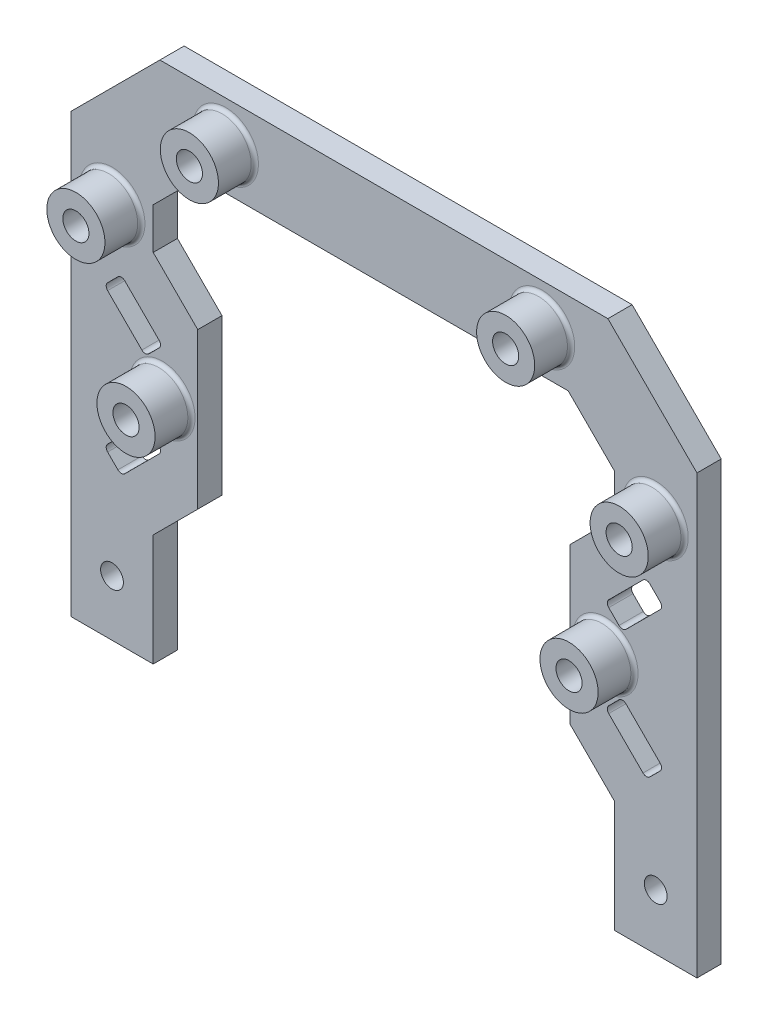
SolidWorks part; units mm, degrees
ref_plane "Front Plane" through (0, 0, 0) normal (0, 0, 1) x (1, 0, 0)
ref_plane "Top Plane" through (0, 0, 0) normal (0, 1, 0) x (1, 0, 0)
ref_plane "Right Plane" through (0, 0, 0) normal (1, 0, 0) x (0, 0, -1)
sketch "Sketch2" plane through (0, 0, 0) normal (0, 0, 1) x (1, 0, 0)
  line L0 (-64.5954, 0) -> (64.5954, 0) construction
  line L2 (-36.0554, 88.6243) -> (36.0554, 88.6243) construction
  line L3 (-38.6151, 31.7729) -> (-47.1004, 23.2876) construction
  line L4 (-47.1004, 73.3367) -> (-38.6151, 64.8514) construction
  line L6 (0, 0) -> (0, 120.7475) construction
  line L8 (-38.0349, 91.6243) -> (0, 91.6243)
  line L9 (-46.2156, 108.6243) -> (0, 108.6243)
  line L14 (46.2156, 108.6243) -> (0, 108.6243)
  line L15 (38.0349, 91.6243) -> (0, 91.6243)
  line L16 (-57.3534, 54.5983) -> (-42.8577, 69.094) construction
  line L21 (-42.8577, 27.5303) -> (-57.3534, 42.026) construction
  line L22 (42.8577, 27.5303) -> (57.3534, 42.026) construction
  line L23 (-46.2156, 108.6243) -> (-64.5954, 90.2445)
  line L24 (-47.5954, 73.5488) -> (-47.5954, 82.0638)
  line L25 (-38.0349, 91.6243) -> (-47.5954, 82.0638)
  line L26 (-64.5954, 0) -> (-47.5954, 0)
  line L27 (-38.403, 64.3564) -> (-38.403, 32.2679)
  line L28 (-47.5954, 23.0755) -> (-38.403, 32.2679)
  line L29 (-38.403, 64.3564) -> (-47.5954, 73.5488)
  line L30 (-47.5954, 23.0755) -> (-47.5954, 0)
  line L31 (-64.5954, 0) -> (-64.5954, 90.2445)
  line L32 (42.7586, 68.9949) -> (57.3534, 54.5983) construction
  line L33 (64.5954, 0) -> (64.5954, 90.2445)
  line L34 (47.5954, 23.0755) -> (47.5954, 0)
  line L35 (38.403, 64.3564) -> (47.5954, 73.5488)
  line L36 (47.5954, 23.0755) -> (38.403, 32.2679)
  line L37 (38.403, 64.3564) -> (38.403, 32.2679)
  line L38 (64.5954, 0) -> (47.5954, 0)
  line L39 (38.0349, 91.6243) -> (47.5954, 82.0638)
  line L40 (47.5954, 73.5488) -> (47.5954, 82.0638)
  line L41 (46.2156, 108.6243) -> (64.5954, 90.2445)
  line L42 (-53.1108, 46.2686) -> (-61.5961, 37.7833) construction
  line L43 (-61.5961, 58.841) -> (-53.1108, 50.3557) construction
  point P34 (0, 0)
  point P38 (0, 108.6243)
  point P39 (0, 91.6243)
  point P40 (-42.9992, 27.6717)
  dimension "D2" = 17
  dimension "D4" = 13
  dimension "D3" = 0.2
  dimension "D5" = 17
  dimension "D6" = 45
  dimension "D7" = 13
  dimension "D8" = 3
  dimension "D10" = 0.2
extrude "Boss-Extrude2" add sketch "Sketch2" against normal blind 5
sketch "Sketch4" plane through (0, 0, 0) normal (0, 0, 1) x (1, 0, 0)
  line L0 (56.0954, 0) -> (55.4055, 99.4344) construction
  line L1 (55.4055, 99.4344) -> (-55.4055, 99.4344) construction
  line L2 (-55.4055, 99.4344) -> (-56.0954, 0) construction
  line L3 (-38.403, 48.3122) -> (-64.4972, 48.3122) construction
  line L4 (38.403, 48.3122) -> (64.4972, 48.3122) construction
  line L5 (38.403, 64.3564) -> (38.403, 32.2679) construction
  line L6 (-47.5954, 0) -> (-64.5954, 0) construction
  line L8 (-46.2156, 108.6243) -> (-64.5954, 90.2445) construction
  line L9 (64.5954, 90.2445) -> (46.2156, 108.6243) construction
  line L10 (-38.403, 32.2679) -> (-38.403, 64.3564) construction
  line L11 (42.9992, 27.6717) -> (42.9992, 68.9526) construction
  line L12 (47.5954, 73.5488) -> (38.403, 64.3564) construction
  line L13 (38.403, 32.2679) -> (47.5954, 23.0755) construction
  line L14 (47.5954, 77.8063) -> (64.4972, 77.8063) construction
  line L15 (47.5954, 82.0638) -> (47.5954, 73.5488) construction
  line L16 (31.2176, 108.8703) -> (31.2176, 91.6243) construction
  line L17 (0, 108.6243) -> (0, 91.6243) construction
  line L19 (47.5954, 0) -> (64.5954, 0) construction
  circle A0 centre (45.703, 48.3122) radius 6
  circle A1 centre (56.0463, 77.8063) radius 6
  circle A2 centre (32.6276, 100.1896) radius 6
  circle A3 centre (-32.6276, 100.1896) radius 6
  circle A4 centre (-45.703, 48.3122) radius 6
  circle A5 centre (-56.0463, 77.8063) radius 6
  point P11 (56.0463, 77.8063)
  dimension "D1" = 12
  dimension "D3" = 7.3
  dimension "D2" = 12
  dimension "D5" = 12
  dimension "D4" = 15
extrude "Boss-Extrude3" add sketch "Sketch4" along normal blind 7.5
fillet "Fillet1" radius 0.75 6 edges at (26.6276, 100.1896, 0) (50.0463, 77.8063, 0) (39.703, 48.3122, 0) (-51.703, 48.3122, 0) (-62.0463, 77.8063, 0) (-38.6276, 100.1896, 0)
sketch "Sketch5" plane through (0, 0, -5) normal (0, 0, -1) x (-1, 0, 0)
  circle A0 centre (56.0954, 11.5) radius 2.35 construction
  circle A1 centre (-56.0954, 11.5) radius 2.35 construction
  circle A2 centre (56.0954, 11.5) radius 2.35
  circle A3 centre (-56.0954, 11.5) radius 2.35
extrude "Cut-Extrude1" cut sketch "Sketch5" against normal up to surface (5 mm away) up to face at (25.8776, 100.1896, 0)
sketch "Sketch6" plane through (0, 0, 7.5) normal (0, 0, 1) x (1, 0, 0)
  circle A0 centre (32.6276, 100.1896) radius 6 construction
  circle A1 centre (45.703, 48.3122) radius 6 construction
  circle A2 centre (56.0463, 77.8063) radius 6 construction
  circle A3 centre (-32.6276, 100.1896) radius 6 construction
  circle A4 centre (-56.0463, 77.8063) radius 6 construction
  circle A5 centre (-45.703, 48.3122) radius 6 construction
  circle A6 centre (32.6276, 100.1896) radius 6 construction
  circle A7 centre (45.703, 48.3122) radius 6 construction
  circle A8 centre (56.0463, 77.8063) radius 6 construction
  circle A9 centre (-32.6276, 100.1896) radius 6 construction
  circle A10 centre (-56.0463, 77.8063) radius 6 construction
  circle A11 centre (-45.703, 48.3122) radius 6 construction
  circle A12 centre (-45.703, 48.3122) radius 2.7
  circle A14 centre (-32.6276, 100.1896) radius 2.7
  circle A15 centre (32.6276, 100.1896) radius 2.7
  circle A16 centre (56.0463, 77.8063) radius 2.7
  circle A17 centre (45.703, 48.3122) radius 2.7
  circle A18 centre (-56.0463, 77.8063) radius 2.7
  dimension "D1" = 5.4
extrude "Cut-Extrude2" cut sketch "Sketch6" against normal up to surface (12.5 mm away) up to face at (-58.4454, 11.5, -5)
sketch "Sketch7" plane through (0, 0, -5) normal (0, 0, -1) x (-1, 0, 0)
  line L0 (45.6862, 57.7803) -> (49.2217, 54.2448) construction
  line L1 (49.2217, 54.2448) -> (57.707, 62.7301) construction
  line L2 (57.707, 62.7301) -> (54.1715, 66.2656) construction
  line L3 (54.1715, 66.2656) -> (45.6862, 57.7803) construction
  line L4 (54.1715, 30.3587) -> (57.707, 33.8943) construction
  line L5 (57.707, 33.8943) -> (49.2217, 42.3795) construction
  line L6 (49.2217, 42.3795) -> (45.6862, 38.844) construction
  line L7 (45.6862, 38.844) -> (54.1715, 30.3587) construction
  line L8 (-54.1715, 66.2656) -> (-57.707, 62.7301) construction
  line L9 (-57.707, 62.7301) -> (-49.2217, 54.2448) construction
  line L10 (-49.2217, 54.2448) -> (-45.6862, 57.7803) construction
  line L11 (-45.6862, 57.7803) -> (-54.1715, 66.2656) construction
  line L12 (-45.6862, 38.844) -> (-49.2217, 42.3795) construction
  line L13 (-49.2217, 42.3795) -> (-57.707, 33.8943) construction
  line L14 (-57.707, 33.8943) -> (-54.1715, 30.3587) construction
  line L15 (-54.1715, 30.3587) -> (-45.6862, 38.844) construction
  line L16 (45.6862, 57.7803) -> (49.2217, 54.2448)
  line L17 (49.2217, 54.2448) -> (57.707, 62.7301)
  line L18 (57.707, 62.7301) -> (54.1715, 66.2656)
  line L19 (54.1715, 66.2656) -> (45.6862, 57.7803)
  line L20 (54.1715, 30.3587) -> (57.707, 33.8943)
  line L21 (57.707, 33.8943) -> (49.2217, 42.3795)
  line L22 (49.2217, 42.3795) -> (45.6862, 38.844)
  line L23 (45.6862, 38.844) -> (54.1715, 30.3587)
  line L24 (-54.1715, 66.2656) -> (-57.707, 62.7301)
  line L25 (-57.707, 62.7301) -> (-49.2217, 54.2448)
  line L26 (-49.2217, 54.2448) -> (-45.6862, 57.7803)
  line L27 (-45.6862, 57.7803) -> (-54.1715, 66.2656)
  line L28 (-45.6862, 38.844) -> (-49.2217, 42.3795)
  line L29 (-49.2217, 42.3795) -> (-57.707, 33.8943)
  line L30 (-57.707, 33.8943) -> (-54.1715, 30.3587)
  line L31 (-54.1715, 30.3587) -> (-45.6862, 38.844)
extrude "Cut-Extrude3" cut sketch "Sketch7" against normal up to surface (5 mm away) up to face at (-58.4454, 11.5, 0)
fillet "Fillet2" radius 1 16 edges at (-49.2217, 54.2448, -2.5) (-57.707, 62.7301, -2.5) (-54.1715, 66.2656, -2.5) (-45.6862, 57.7803, -2.5) (-49.2217, 42.3795, -2.5) (-45.6862, 38.844, -2.5) (-54.1715, 30.3587, -2.5) (-57.707, 33.8943, -2.5) (54.1715, 30.3587, -2.5) (57.707, 33.8943, -2.5) (49.2217, 42.3795, -2.5) (45.6862, 38.844, -2.5) (45.6862, 57.7803, -2.5) (49.2217, 54.2448, -2.5) (57.707, 62.7301, -2.5) (54.1715, 66.2656, -2.5)
